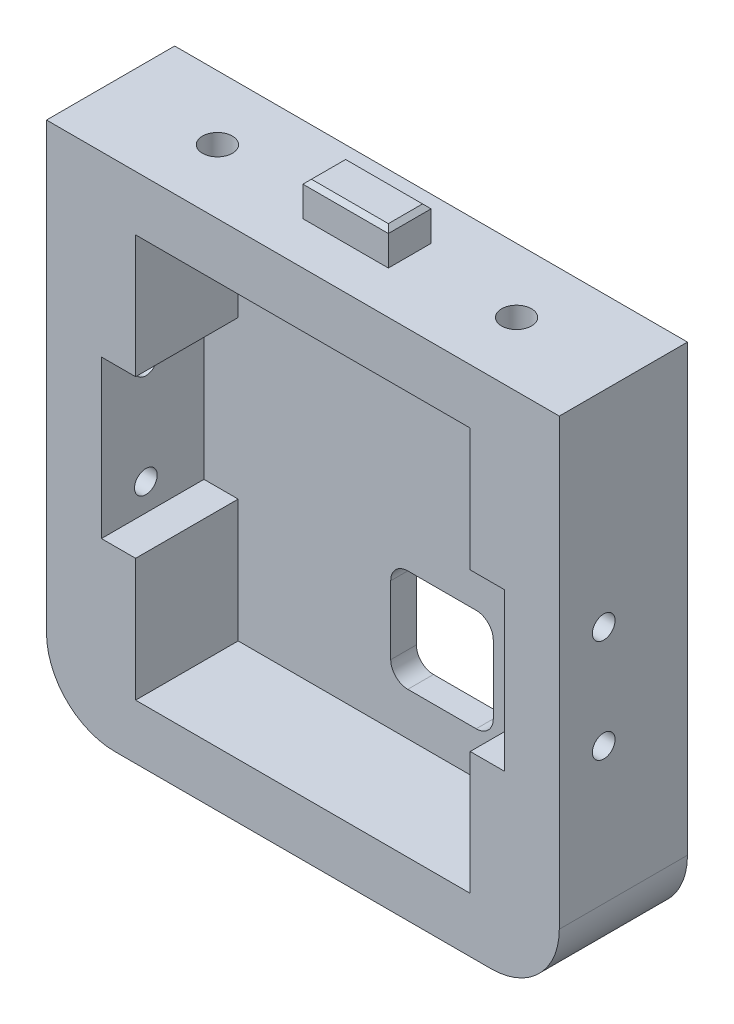
SolidWorks part; units mm, degrees
ref_plane "前视基准面" through (0, 0, 0) normal (0, 0, 1) x (1, 0, 0)
ref_plane "上视基准面" through (0, 0, 0) normal (0, 1, 0) x (1, 0, 0)
ref_plane "右视基准面" through (0, 0, 0) normal (1, 0, 0) x (0, 0, -1)
sketch "草图3" plane through (0, 0, 0) normal (0, 0, 1) x (1, 0, 0)
  line L1 (-30, 30) -> (30, 30)
  line L2 (-30, 30) -> (-30, -30)
  line L3 (-30, -30) -> (30, -30)
  line L4 (30, 30) -> (30, -30)
  line L5 (-30, 30) -> (30, -30) construction
  line L6 (-30, -30) -> (30, 30) construction
  point P0 (0, 0)
  dimension "D1" = 60
  dimension "D2" = 60
extrude "凸台-拉伸1" add sketch "草图3" along normal blind 15
sketch "草图4" plane through (0, 0, 15) normal (0, 0, 1) x (1, 0, 0)
  line L1 (-23.575, 23.575) -> (23.575, 23.575)
  line L2 (-23.575, 23.575) -> (-23.575, -23.575)
  line L3 (-23.575, -23.575) -> (23.575, -23.575)
  line L4 (23.575, 23.575) -> (23.575, -23.575)
  line L5 (-23.575, 23.575) -> (23.575, -23.575) construction
  line L6 (-23.575, -23.575) -> (23.575, 23.575) construction
  point P0 (0, 0)
  dimension "D1" = 47.15
extrude "切除-拉伸1" cut sketch "草图4" against normal blind 12
sketch "草图5" plane through (-30, 0, 0) normal (-1, 0, 0) x (0, 0, 1)
  line L0 (9.8, 30) -> (9.8, -30) construction
  line L1 (15, 30) -> (0, 30) construction
  line L2 (15, -30) -> (0, -30) construction
  line L3 (15, 30) -> (15, -30) construction
  line L4 (0, 0) -> (26.5643, 0) construction
  circle A0 centre (9.8, 6.025) radius 1.325
  circle A1 centre (9.8, -6.025) radius 1.325
  dimension "D2" = 12.05
  dimension "D3" = 2.65
  dimension "D1" = 5.2
extrude "切除-拉伸2" cut sketch "草图5" against normal through all
sketch "草图6" plane through (0, 0, 15) normal (0, 0, 1) x (1, 0, 0)
  line L0 (0, 0) -> (0, 23.575) construction
  line L1 (-23.575, 23.575) -> (-19.575, 23.575)
  line L2 (-23.575, 23.575) -> (-23.575, 9.2)
  line L3 (-23.575, 9.2) -> (-19.575, 9.2)
  line L4 (-19.575, 23.575) -> (-19.575, 9.2)
  line L5 (23.575, 23.575) -> (-23.575, 23.575) construction
  line L6 (0, 0) -> (14.8073, 0) construction
  line L7 (19.575, 23.575) -> (19.575, 9.2)
  line L8 (23.575, 9.2) -> (19.575, 9.2)
  line L9 (23.575, 23.575) -> (23.575, 9.2)
  line L10 (23.575, 23.575) -> (19.575, 23.575)
  line L11 (23.575, -23.575) -> (19.575, -23.575)
  line L12 (23.575, -23.575) -> (23.575, -9.2)
  line L13 (23.575, -9.2) -> (19.575, -9.2)
  line L14 (19.575, -23.575) -> (19.575, -9.2)
  line L15 (-19.575, -23.575) -> (-19.575, -9.2)
  line L16 (-23.575, -9.2) -> (-19.575, -9.2)
  line L17 (-23.575, -23.575) -> (-23.575, -9.2)
  line L18 (-23.575, -23.575) -> (-19.575, -23.575)
  dimension "D1" = 9.2
  dimension "D2" = 4
extrude "凸台-拉伸2" add sketch "草图6" against normal up to next
fillet "圆角1" radius 8 2 edges at (30, -30, 7.5) (-30, -30, 7.5)
sketch "草图11" plane through (0, 30, 0) normal (0, 1, 0) x (1, 0, 0)
  line L0 (-30, -7.5) -> (30, -7.5) construction
  line L1 (-30, -15) -> (-30, 0) construction
  line L2 (30, -15) -> (30, 0) construction
  line L3 (0, 7.8519) -> (0, -27.8021) construction
  circle A1 centre (-17.5, -7.5) radius 1.75
  circle A2 centre (17.5, -7.5) radius 1.75
  dimension "D1" = 3.5
  dimension "D2" = 35
extrude "切除-拉伸5" cut sketch "草图11" against normal blind 5.5
sketch "草图12" plane through (0, -30, 0) normal (0, -1, 0) x (1, 0, 0)
  line L0 (-22, 7.5) -> (22, 7.5) construction
  line L1 (-22, 15) -> (-22, 0) construction
  line L2 (22, 0) -> (22, 15) construction
  line L3 (0, 20.3889) -> (0, -11.9472) construction
  circle A0 centre (-17.5, 7.5) radius 1.4
  circle A1 centre (17.5, 7.5) radius 1.4
  dimension "D1" = 2.8
  dimension "D2" = 35
extrude "切除-拉伸6" cut sketch "草图12" against normal blind 5.5
sketch "草图13" plane through (0, 30, 0) normal (0, 1, 0) x (1, 0, 0)
  line L0 (-17.5, -7.5) -> (17.5, -7.5) construction
  line L2 (-5, -5) -> (5, -5)
  line L3 (-5, -5) -> (-5, -10)
  line L4 (-5, -10) -> (5, -10)
  line L5 (5, -5) -> (5, -10)
  line L6 (-5, -5) -> (5, -10) construction
  line L7 (-5, -10) -> (5, -5) construction
  point P4 (0, -7.5)
  dimension "D1" = 5
  dimension "D2" = 10
extrude "凸台-拉伸3" add sketch "草图13" along normal blind 4
chamfer "倒角1" distance 0.5 angle 45 4 edges at (5, 34, 7.5) (0, 34, 10) (-5, 34, 7.5) (0, 34, 5)
sketch "草图15" plane through (0, 0, 3) normal (0, 0, 1) x (1, 0, 0)
  line L1 (10.275, -18.55) -> (-1.725, -18.55)
  line L2 (10.275, -18.55) -> (10.275, -6.55)
  line L3 (10.275, -6.55) -> (-1.725, -6.55)
  line L4 (-1.725, -18.55) -> (-1.725, -6.55)
  line L5 (10.275, -18.55) -> (-1.725, -6.55) construction
  line L6 (10.275, -6.55) -> (-1.725, -18.55) construction
  point P0 (4.275, -12.55)
  point P5 (4.275, -12.55)
  point P9 (1.7355, 0.7966)
  dimension "D1" = 12
  dimension "D2" = 12
  dimension "D3" = 12.55
  dimension "D4" = 4.275
extrude "切除-拉伸7" cut sketch "草图15" against normal through all
fillet "圆角2" radius 2 4 edges at (10.275, -18.55, 1.5) (-1.725, -18.55, 1.5) (-1.725, -6.55, 1.5) (10.275, -6.55, 1.5)
